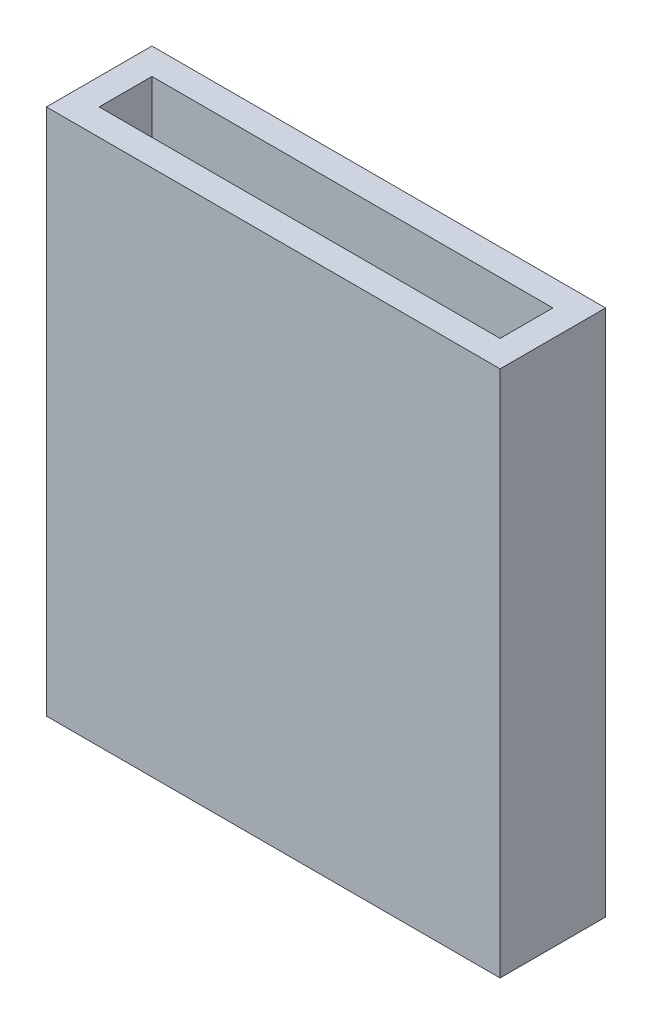
SolidWorks part; units mm, degrees
ref_plane "Front Plane" through (0, 0, 0) normal (0, 0, 1) x (1, 0, 0)
ref_plane "Top Plane" through (0, 0, 0) normal (0, 1, 0) x (1, 0, 0)
ref_plane "Right Plane" through (0, 0, 0) normal (1, 0, 0) x (0, 0, -1)
sketch "Sketch3" plane through (0, 0, 0) normal (0, 0, 1) x (1, 0, 0)
  line L0 (0, 0) -> (86, 0)
  line L1 (86, 0) -> (86, 100)
  line L2 (86, 100) -> (0, 100)
  line L3 (0, 100) -> (0, 0)
  dimension "D1" = 86
  dimension "D2" = 100
extrude "Boss-Extrude1" add sketch "Sketch3" along normal blind 20
sketch "Sketch5" plane through (0, 100, 0) normal (0, 1, 0) x (1, 0, 0)
  line L0 (5, -5) -> (5, -15)
  line L1 (5, -15) -> (81, -15)
  line L2 (81, -15) -> (81, -5)
  line L3 (81, -5) -> (5, -5)
  line L4 (86, 0) -> (0, 0) construction
  line L5 (86, -20) -> (0, -20) construction
  line L6 (0, -20) -> (0, 0) construction
  line L7 (86, -20) -> (86, 0) construction
  dimension "D1" = 5
  dimension "D2" = 5
  dimension "D3" = 5
  dimension "D4" = 5
extrude "Cut-Extrude1" cut sketch "Sketch5" against normal blind 90
sketch "Sketch6" plane through (0, 10, 0) normal (0, 1, 0) x (1, 0, 0)
  circle A0 centre (43, -10) radius 2
  dimension "D1" = 4
extrude "Cut-Extrude2" cut sketch "Sketch6" against normal blind 90
